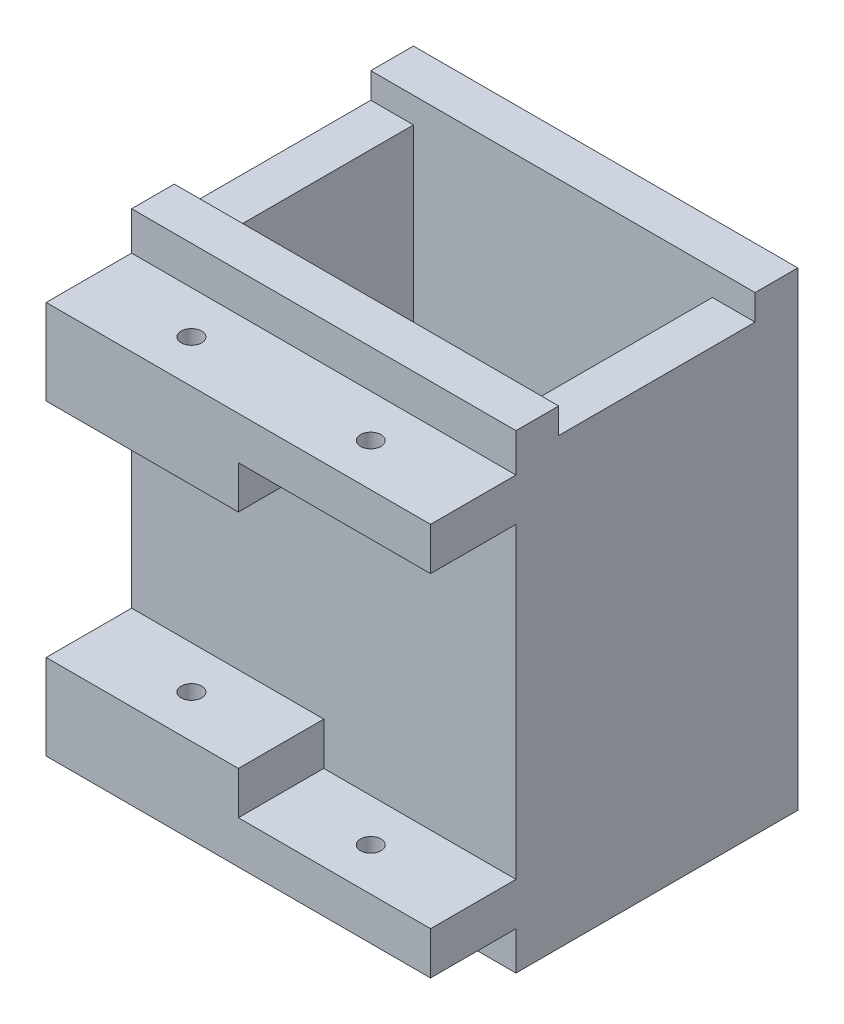
SolidWorks part; units mm, degrees
ref_plane "正面" through (0, 0, 0) normal (0, 0, 1) x (1, 0, 0)
ref_plane "平面" through (0, 0, 0) normal (0, 1, 0) x (1, 0, 0)
ref_plane "右側面" through (0, 0, 0) normal (1, 0, 0) x (0, 0, -1)
sketch "ｽｹｯﾁ1" plane through (0, 0, 0) normal (0, 0, 1) x (1, 0, 0)
  line L1 (-22.5, 25) -> (22.5, 25)
  line L2 (-22.5, 25) -> (-22.5, -25)
  line L3 (-22.5, -25) -> (22.5, -25)
  line L4 (22.5, 25) -> (22.5, -25)
  line L5 (-22.5, 25) -> (22.5, -25) construction
  line L6 (-22.5, -25) -> (22.5, 25) construction
  point P0 (0, 0)
  dimension "D1" = 50
  dimension "D2" = 45
extrude "ﾎﾞｽ - 押し出し1" add sketch "ｽｹｯﾁ1" along normal blind 43
sketch "ｽｹｯﾁ2" plane through (0, 25, 0) normal (0, 1, 0) x (1, 0, 0)
  line L1 (17.5, -5) -> (-17.5, -5)
  line L2 (17.5, -5) -> (17.5, -28)
  line L3 (17.5, -28) -> (-17.5, -28)
  line L4 (-17.5, -5) -> (-17.5, -28)
  line L5 (22.5, 0) -> (-22.5, 0) construction
  point P6 (0, -5)
  dimension "D1" = 5
  dimension "D2" = 23
  dimension "D3" = 35
extrude "ｶｯﾄ - 押し出し1" cut sketch "ｽｹｯﾁ2" against normal through all
sketch "ｽｹｯﾁ3" plane through (0, -25, 0) normal (0, -1, 0) x (1, 0, 0)
  line L1 (22.5, 43) -> (-22.5, 43)
  line L2 (22.5, 43) -> (22.5, 0)
  line L3 (22.5, 0) -> (-22.5, 0)
  line L4 (-22.5, 43) -> (-22.5, 0)
extrude "ﾎﾞｽ - 押し出し2" add sketch "ｽｹｯﾁ3" along normal blind 5
sketch "ｽｹｯﾁ4" plane through (22.5, 0, 0) normal (1, 0, 0) x (0, 0, -1)
  line L0 (-43, -30) -> (-43, 25) construction
  line L1 (-43, 10.5) -> (-33, 10.5)
  line L2 (-43, 10.5) -> (-43, -15.5)
  line L3 (-43, -15.5) -> (-33, -15.5)
  line L4 (-33, 10.5) -> (-33, -15.5)
  line L5 (0, -30) -> (0, 25) construction
  line L7 (-33, -25.5) -> (-43, -25.5)
  line L8 (-33, -25.5) -> (-33, -30)
  line L9 (-33, -30) -> (-43, -30)
  line L10 (-43, -25.5) -> (-43, -30)
  line L11 (-43, 25) -> (-33, 25)
  line L12 (-43, 25) -> (-43, 20.5)
  line L13 (-43, 20.5) -> (-33, 20.5)
  line L14 (-33, 25) -> (-33, 20.5)
  point P9 (0, -2.5)
  point P10 (-33, -2.5)
  dimension "D1" = 10
  dimension "D2" = 26
  dimension "D3" = 10
  dimension "D4" = 10
extrude "ｶｯﾄ - 押し出し2" cut sketch "ｽｹｯﾁ4" against normal through all
sketch "ｽｹｯﾁ5" plane through (0, 0, 43) normal (0, 0, 1) x (1, 0, 0)
  line L0 (22.5, 10.5) -> (22.5, 20.5) construction
  line L1 (22.5, 15.5) -> (0, 15.5)
  line L2 (22.5, 15.5) -> (22.5, 10.5)
  line L3 (22.5, 10.5) -> (0, 10.5)
  line L4 (0, 15.5) -> (0, 10.5)
  line L5 (-22.5, 10.5) -> (22.5, 10.5) construction
  line L6 (-22.5, 20.5) -> (22.5, 20.5) construction
  point P10 (0, 20.5)
extrude "ｶｯﾄ - 押し出し3" cut sketch "ｽｹｯﾁ5" against normal up to surface (10 mm away) up to face at (0, -2.5, 33)
hole_wizard "M2 すきま穴1" positions "ｽｹｯﾁ6" profile "ｽｹｯﾁ7" hole size "M2" standard "JIS" end condition through all
sketch "ｽｹｯﾁ6" plane through (0, 20.5, 0) normal (0, 1, 0) x (1, 0, 0)
  line L2 (-22.5, -43) -> (-22.5, -33) construction
  line L3 (-10.5, -38) -> (10.5, -38) construction
  line L5 (-22.5, -43) -> (22.5, -43) construction
  point P5 (-10.5, -38)
  point P7 (10.5, -38)
  point P13 (-22.5, -38)
  point P20 (0, -43)
  point P21 (0, -38)
  dimension "D1" = 21
sketch "ｽｹｯﾁ7" plane through (-10.5, 20.5, 38) normal (1, 0, 0) x (0, 0, 1)
  line L0 (0, 0) -> (0, 50.5)
  line L1 (0, 50.5) -> (1.2, 50.5)
  line L2 (1.2, 50.5) -> (1.2, 0)
  line L5 (1.2, 0) -> (0, 0)
  line L11 (0, -6.35) -> (0, 107.95) construction
  dimension "通し穴の直径" = 2.4
  dimension "通し穴の深さ" = 50.5
sketch "ｽｹｯﾁ8" plane through (0, 25, 0) normal (0, 1, 0) x (1, 0, 0)
  line L0 (22.5, -33) -> (22.5, 0) construction
  line L1 (22.5, -5) -> (-22.5, -5)
  line L2 (22.5, -5) -> (22.5, -28)
  line L3 (22.5, -28) -> (-22.5, -28)
  line L4 (-22.5, -5) -> (-22.5, -28)
  line L5 (-22.5, -33) -> (-22.5, 0) construction
  line L6 (-17.5, -28) -> (17.5, -28) construction
  line L7 (17.5, -5) -> (-17.5, -5) construction
extrude "ｶｯﾄ - 押し出し4" cut sketch "ｽｹｯﾁ8" against normal blind 3
sketch "ｽｹｯﾁ11" plane through (0, 0, 43) normal (0, 0, 1) x (1, 0, 0)
  line L0 (-22.5, -15.5) -> (-22.5, -25.5) construction
  line L1 (22.5, -15.5) -> (0, -15.5)
  line L2 (22.5, -15.5) -> (22.5, -20.5)
  line L3 (22.5, -20.5) -> (0, -20.5)
  line L4 (0, -15.5) -> (0, -20.5)
  point P5 (0, 0)
  point P8 (-22.5, -20.5)
extrude "ｶｯﾄ - 押し出し5" cut sketch "ｽｹｯﾁ11" against normal up to surface (10 mm away) up to face at (0, 3.5, 33)
